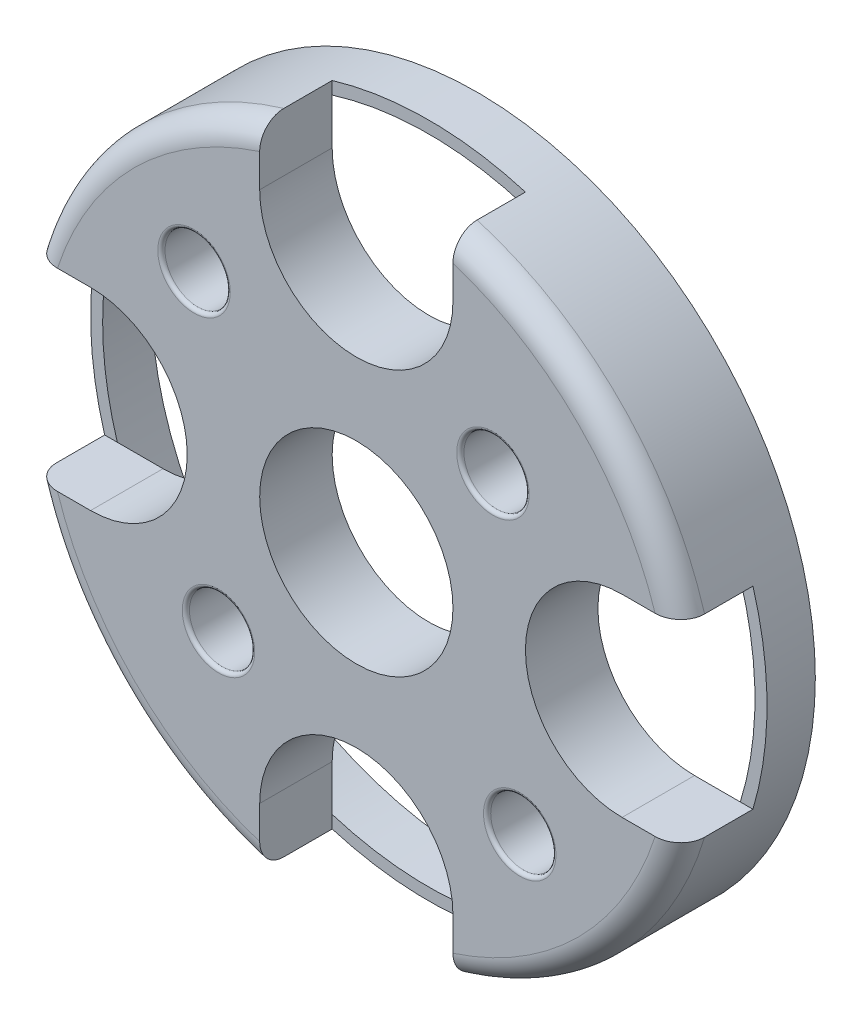
SolidWorks part; units mm, degrees
ref_plane "Front Plane" through (0, 0, 0) normal (0, 0, 1) x (1, 0, 0)
ref_plane "Top Plane" through (0, 0, 0) normal (0, 1, 0) x (1, 0, 0)
ref_plane "Right Plane" through (0, 0, 0) normal (1, 0, 0) x (0, 0, -1)
sketch "Sketch1" plane through (0, 0, 0) normal (0, 0, 1) x (1, 0, 0)
  line L0 (-39.8033, 16.7214) -> (-41.5697, 16.7214)
  line L1 (-39.8033, 7.7214) -> (-41.5697, 7.7214)
  circle A0 centre (0, 0) radius 14
  circle A1 centre (-6.7175, 6.7175) radius 1.5
  circle A2 centre (6.7175, -6.7175) radius 1.5
  circle A3 centre (5.6569, 5.6569) radius 1.5
  circle A4 centre (-5.6569, -5.6569) radius 1.5
  arc A5 (-39.8033, 16.7214) -> (-39.8033, 7.7214) centre (-39.8033, 12.2214) cw
  circle A9 centre (0, 0) radius 4
  point P40 (0, 0)
extrude "Boss-Extrude1" add sketch "Sketch1" along normal blind 5 contours A0 A9 A4 A3 A2 A1
sketch "Sketch13" plane through (0, 0, 5) normal (0, 0, 1) x (1, 0, 0)
  line L0 (-11, 4) -> (-13.4164, 4)
  line L1 (4, 11) -> (4, 13.4164)
  line L2 (-11, -4) -> (-13.4164, -4)
  line L3 (-4, 11) -> (-4, 13.4164)
  line L4 (11, -4) -> (13.4164, -4)
  line L5 (11, 4) -> (13.4164, 4)
  line L6 (-4, -11) -> (-4, -13.4164)
  line L7 (4, -11) -> (4, -13.4164)
  arc A0 (-11, 4) -> (-11, -4) centre (-11, 0) cw
  arc A1 (-13.4164, -4) -> (-13.4164, 4) centre (0, 0) cw
  circle A2 centre (0, 0) radius 14 construction
  arc A3 (4, 11) -> (-4, 11) centre (0, 11) cw
  arc A4 (-4, 13.4164) -> (4, 13.4164) centre (0, 0) cw
  arc A5 (11, -4) -> (11, 4) centre (11, 0) cw
  arc A6 (13.4164, 4) -> (13.4164, -4) centre (0, 0) cw
  arc A7 (-4, -11) -> (4, -11) centre (0, -11) cw
  arc A8 (4, -13.4164) -> (-4, -13.4164) centre (0, 0) cw
  point P31 (0, 0)
extrude "Cut-Extrude4" cut sketch "Sketch13" against normal blind 3
sketch "Sketch14" plane through (0, 0, 0) normal (0, 0, -1) x (-1, 0, 0)
  circle A0 centre (0, 0) radius 13.5
extrude "Cut-Extrude5" cut sketch "Sketch14" against normal blind 2
fillet "Fillet2" radius 1 4 edges at (-9.8995, 9.8995, 5) (9.8995, 9.8995, 5) (-9.8995, -9.8995, 5) (9.8995, -9.8995, 5)
sketch "Sketch16" plane through (0, 0, 2) normal (0, 0, -1) x (-1, 0, 0)
  circle A0 centre (6.7175, 6.7175) radius 1.5
extrude "Boss-Extrude2" add sketch "Sketch16" along normal blind 1 and the other way blind 3
sketch "Sketch17" plane through (0, 0, 2) normal (0, 0, -1) x (-1, 0, 0)
  circle A0 centre (-5.6569, 5.6569) radius 1.5
  circle A1 centre (5.705, -5.6719) radius 1.5504
  circle A2 centre (-6.7635, -6.7255) radius 1.5467
extrude "Boss-Extrude4" add sketch "Sketch17" along normal blind 1 and the other way blind 3
hole_wizard "CSK for M2.5 Flat Head Machine Screw1" positions "3DSketch1" profile "Sketch27" countersink size "M2.5" standard "ANSI Metric" end condition through all
sketch3d "3DSketch1"
  line L0 (-6.7175, 6.7175, 2) -> (-6.7175, 6.7175, 1) construction
  point P0 (-6.7175, 6.7175, 1)
sketch "Sketch27" plane through (-6.7175, 6.7175, 1) normal (1, 0, 0) x (0, 1, 0)
  line L0 (0, 0) -> (0, 4.0636)
  line L1 (0, 4.0636) -> (1.35, 4.0636)
  line L2 (1.35, 4.0636) -> (1.35, 1.4)
  line L3 (1.35, 1.4) -> (2.75, 0)
  line L5 (2.75, 0) -> (0, 0)
  line L6 (-1.35, 1.4) -> (-2.75, 0) construction
  line L11 (0, -6.35) -> (0, 107.95) construction
  dimension "Thru Hole Dia." = 2.7
  dimension "Thru Hole Depth" = 4.0636
  dimension "Near C'Sink Dia." = 5.5
  dimension "Near C'Sink Angle" = 90
hole_wizard "CSK for M2.5 Flat Head Machine Screw2" positions "3DSketch2" profile "Sketch28" countersink size "M2.5" standard "ANSI Metric" end condition through all
sketch3d "3DSketch2"
  line L0 (5.6569, 5.6569, 2) -> (5.6569, 5.6569, 1) construction
  point P0 (5.6569, 5.6569, 1)
sketch "Sketch28" plane through (5.6569, 5.6569, 1) normal (1, 0, 0) x (0, 1, 0)
  line L0 (0, 0) -> (0, 4.0636)
  line L1 (0, 4.0636) -> (1.35, 4.0636)
  line L2 (1.35, 4.0636) -> (1.35, 1.4)
  line L3 (1.35, 1.4) -> (2.75, 0)
  line L5 (2.75, 0) -> (0, 0)
  line L6 (-1.35, 1.4) -> (-2.75, 0) construction
  line L11 (0, -6.35) -> (0, 107.95) construction
  dimension "Thru Hole Dia." = 2.7
  dimension "Thru Hole Depth" = 4.0636
  dimension "Near C'Sink Dia." = 5.5
  dimension "Near C'Sink Angle" = 90
hole_wizard "CSK for M2.5 Flat Head Machine Screw3" positions "3DSketch3" profile "Sketch29" countersink size "M2.5" standard "ANSI Metric" end condition through all
sketch3d "3DSketch3"
  line L0 (6.7635, -6.7255, 2) -> (6.7635, -6.7255, 1) construction
  point P0 (6.7635, -6.7255, 1)
sketch "Sketch29" plane through (6.7635, -6.7255, 1) normal (1, 0, 0) x (0, 1, 0)
  line L0 (0, 0) -> (0, 4.0636)
  line L1 (0, 4.0636) -> (1.35, 4.0636)
  line L2 (1.35, 4.0636) -> (1.35, 1.4)
  line L3 (1.35, 1.4) -> (2.75, 0)
  line L5 (2.75, 0) -> (0, 0)
  line L6 (-1.35, 1.4) -> (-2.75, 0) construction
  line L11 (0, -6.35) -> (0, 107.95) construction
  dimension "Thru Hole Dia." = 2.7
  dimension "Thru Hole Depth" = 4.0636
  dimension "Near C'Sink Dia." = 5.5
  dimension "Near C'Sink Angle" = 90
hole_wizard "CSK for M2.5 Flat Head Machine Screw4" positions "3DSketch4" profile "Sketch30" countersink size "M2.5" standard "ANSI Metric" end condition through all
sketch3d "3DSketch4"
  line L0 (-5.705, -5.6719, 2) -> (-5.705, -5.6719, 1) construction
  point P0 (-5.705, -5.6719, 1)
sketch "Sketch30" plane through (-5.705, -5.6719, 1) normal (1, 0, 0) x (0, 1, 0)
  line L0 (0, 0) -> (0, 4.0636)
  line L1 (0, 4.0636) -> (1.35, 4.0636)
  line L2 (1.35, 4.0636) -> (1.35, 1.4)
  line L3 (1.35, 1.4) -> (2.75, 0)
  line L5 (2.75, 0) -> (0, 0)
  line L6 (-1.35, 1.4) -> (-2.75, 0) construction
  line L11 (0, -6.35) -> (0, 107.95) construction
  dimension "Thru Hole Dia." = 2.7
  dimension "Thru Hole Depth" = 4.0636
  dimension "Near C'Sink Dia." = 5.5
  dimension "Near C'Sink Angle" = 90
fillet "Fillet3" radius 0.15 4 edges at (8.1135, -6.7255, 5) (7.0069, 5.6569, 5) (-5.3675, 6.7175, 5) (-4.355, -5.6719, 5)
